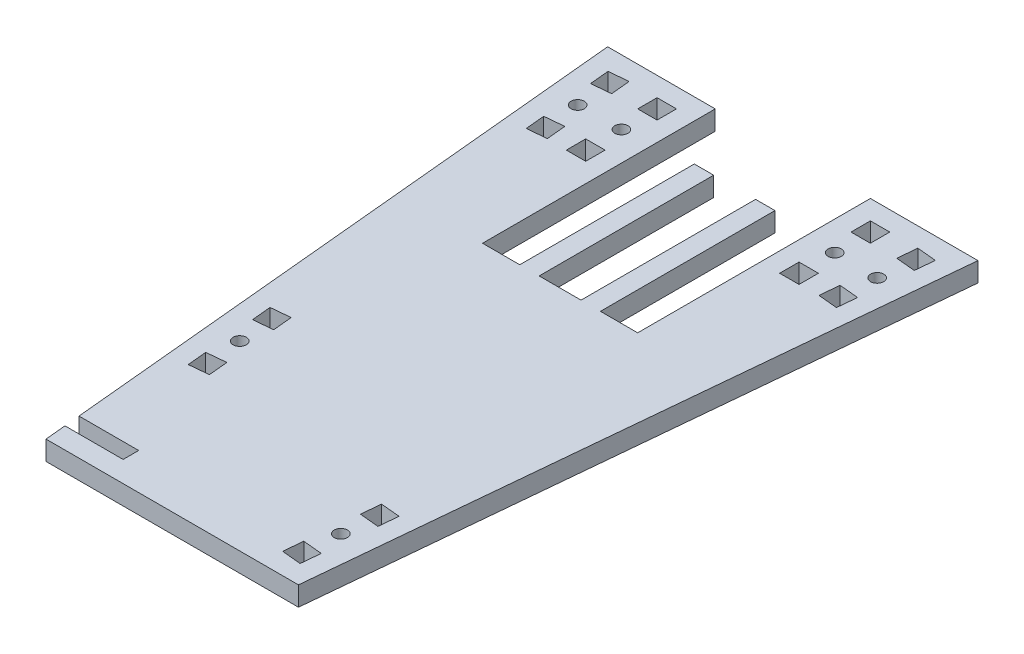
SolidWorks part; units mm, degrees
ref_plane "Front Plane" through (0, 0, 0) normal (0, 0, 1) x (1, 0, 0)
ref_plane "Top Plane" through (0, 0, 0) normal (0, 1, 0) x (1, 0, 0)
ref_plane "Right Plane" through (0, 0, 0) normal (1, 0, 0) x (0, 0, -1)
sketch "Sketch1" plane through (0, 0, 0) normal (0, 1, 0) x (1, 0, 0)
  line L0 (0, 0) -> (0, -183.008) construction
  line L1 (-47.8759, 76.2) -> (-25.4, 76.2)
  line L2 (47.8759, 76.2) -> (28.575, -127) construction
  line L3 (-47.8759, 76.2) -> (-28.575, -127) construction
  line L4 (38.1, 40.132) -> (44.45, 40.132) construction
  line L5 (-47.8759, 76.2) -> (-60.6331, 76.2)
  line L6 (-41.9836, -120.142) -> (-11.3629, -120.142) construction
  line L7 (-57.15, 0) -> (57.15, 0) construction
  line L8 (31.75, 76.2) -> (31.75, 40.132) construction
  line L9 (-31.75, 76.2) -> (-31.75, 40.132) construction
  line L10 (6.858, 57.15) -> (6.858, 0) construction
  line L11 (-6.858, 57.15) -> (-6.858, 0) construction
  line L12 (-6.858, 57.15) -> (-6.858, 0)
  line L13 (-6.858, 0) -> (6.858, 0)
  line L14 (6.858, 0) -> (6.858, 57.15)
  line L15 (6.858, 57.15) -> (13.208, 57.15)
  line L16 (-41.9836, -120.142) -> (-22.9336, -120.142)
  line L17 (-22.9336, -120.142) -> (-22.9336, -115.062)
  line L18 (13.208, 57.15) -> (13.208, 0)
  line L19 (13.208, 0) -> (25.4, 0)
  line L20 (25.4, 0) -> (25.4, 76.2)
  line L21 (25.4, 76.2) -> (47.8759, 76.2)
  line L22 (-25.4, 0) -> (-25.4, 76.2)
  line L23 (-13.208, 0) -> (-25.4, 0)
  line L24 (-13.208, 57.15) -> (-13.208, 0)
  line L25 (-6.858, 0) -> (-6.858, 57.15)
  line L26 (-13.208, 57.15) -> (-6.858, 57.15)
  line L27 (-22.9336, -115.062) -> (-42.4661, -115.062)
  line L28 (-41.9836, -120.142) -> (-41.3322, -127)
  line L29 (47.8759, 76.2) -> (60.6331, 76.2)
  line L30 (60.6331, 76.2) -> (41.3322, -127)
  line L31 (-28.575, -127) -> (0, -127)
  line L32 (0, -127) -> (28.575, -127)
  line L33 (28.575, -127) -> (41.3322, -127)
  line L34 (-60.6331, 76.2) -> (-42.4661, -115.062)
  line L35 (-28.575, -127) -> (-41.3322, -127)
  line L36 (-38.5725, -88.9) -> (-32.251, -88.2995) construction
  line L37 (34.9536, -127) -> (28.632, -126.3995) construction
  line L38 (35.554, -120.6785) -> (34.9536, -127) construction
  line L39 (-39.173, -82.5785) -> (-38.5725, -88.9) construction
  point P0 (0, 0)
  line B0 (34.925, 40.132) -> (34.925, 69.85) construction
  line B1 (32.766, 54.991) -> (37.084, 54.991) construction
  line B2 (31.75, 63.5) -> (38.1, 63.5)
  line B3 (31.75, 63.5) -> (31.75, 69.85)
  line B4 (31.75, 69.85) -> (38.1, 69.85)
  line B5 (38.1, 63.5) -> (38.1, 69.85)
  line B6 (31.75, 63.5) -> (38.1, 69.85) construction
  line B7 (31.75, 69.85) -> (38.1, 63.5) construction
  line B8 (31.75, 40.132) -> (38.1, 46.482) construction
  line B9 (31.75, 46.482) -> (38.1, 40.132) construction
  line B10 (38.1, 46.482) -> (38.1, 40.132)
  line B11 (31.75, 40.132) -> (38.1, 40.132)
  line B12 (31.75, 46.482) -> (31.75, 40.132)
  line B13 (31.75, 46.482) -> (38.1, 46.482)
  circle B14 centre (34.925, 54.991) radius 2.159
  line B15 (-34.925, 40.132) -> (-34.925, 69.85) construction
  line B16 (-32.766, 54.991) -> (-37.084, 54.991) construction
  line B17 (-31.75, 63.5) -> (-38.1, 63.5)
  line B18 (-31.75, 63.5) -> (-31.75, 69.85)
  line B19 (-31.75, 69.85) -> (-38.1, 69.85)
  line B20 (-38.1, 63.5) -> (-38.1, 69.85)
  line B21 (-31.75, 63.5) -> (-38.1, 69.85) construction
  line B22 (-31.75, 69.85) -> (-38.1, 63.5) construction
  line B23 (-31.75, 40.132) -> (-38.1, 46.482) construction
  line B24 (-31.75, 46.482) -> (-38.1, 40.132) construction
  line B25 (-38.1, 46.482) -> (-38.1, 40.132)
  line B26 (-31.75, 40.132) -> (-38.1, 40.132)
  line B27 (-31.75, 46.482) -> (-31.75, 40.132)
  line B28 (-31.75, 46.482) -> (-38.1, 46.482)
  circle B29 centre (-34.925, 54.991) radius 2.159
  line B30 (47.6261, 39.9934) -> (50.4362, 69.5782) construction
  line B31 (46.8819, 54.99) -> (51.1805, 54.5817) construction
  line B32 (46.675, 63.5569) -> (52.9966, 62.9565)
  line B33 (46.675, 63.5569) -> (47.2755, 69.8785)
  line B34 (47.2755, 69.8785) -> (53.597, 69.278)
  line B35 (52.9966, 62.9565) -> (53.597, 69.278)
  line B36 (46.675, 63.5569) -> (53.597, 69.278) construction
  line B37 (47.2755, 69.8785) -> (52.9966, 62.9565) construction
  line B38 (44.4654, 40.2936) -> (51.3873, 46.0147) construction
  line B39 (45.0658, 46.6152) -> (50.7869, 39.6932) construction
  line B40 (51.3873, 46.0147) -> (50.7869, 39.6932)
  line B41 (44.4654, 40.2936) -> (50.7869, 39.6932)
  line B42 (45.0658, 46.6152) -> (44.4654, 40.2936)
  line B43 (45.0658, 46.6152) -> (51.3873, 46.0147)
  circle B44 centre (49.0312, 54.7858) radius 2.159
  line B45 (32.3933, -120.3782) -> (35.2034, -90.7934) construction
  line B46 (31.649, -105.3817) -> (35.9476, -105.79) construction
  line B47 (31.4421, -96.8147) -> (37.7637, -97.4152)
  line B48 (31.4421, -96.8147) -> (32.0426, -90.4932)
  line B49 (32.0426, -90.4932) -> (38.3641, -91.0936)
  line B50 (37.7637, -97.4152) -> (38.3641, -91.0936)
  line B51 (31.4421, -96.8147) -> (38.3641, -91.0936) construction
  line B52 (32.0426, -90.4932) -> (37.7637, -97.4152) construction
  line B53 (29.2325, -120.078) -> (36.1545, -114.3569) construction
  line B54 (29.8329, -113.7565) -> (35.554, -120.6785) construction
  line B55 (36.1545, -114.3569) -> (35.554, -120.6785)
  line B56 (29.2325, -120.078) -> (35.554, -120.6785)
  line B57 (29.8329, -113.7565) -> (29.2325, -120.078)
  line B58 (29.8329, -113.7565) -> (36.1545, -114.3569)
  circle B59 centre (33.7983, -105.5858) radius 2.159
  line B60 (-36.0122, -82.2782) -> (-38.8223, -52.6934) construction
  line B61 (-35.2679, -67.2817) -> (-39.5666, -67.69) construction
  line B62 (-35.0611, -58.7147) -> (-41.3826, -59.3152)
  line B63 (-35.0611, -58.7147) -> (-35.6615, -52.3932)
  line B64 (-35.6615, -52.3932) -> (-41.9831, -52.9936)
  line B65 (-41.3826, -59.3152) -> (-41.9831, -52.9936)
  line B66 (-35.0611, -58.7147) -> (-41.9831, -52.9936) construction
  line B67 (-35.6615, -52.3932) -> (-41.3826, -59.3152) construction
  line B68 (-32.8514, -81.978) -> (-39.7734, -76.2569) construction
  line B69 (-33.4519, -75.6565) -> (-39.173, -82.5785) construction
  line B70 (-39.7734, -76.2569) -> (-39.173, -82.5785)
  line B71 (-32.8514, -81.978) -> (-39.173, -82.5785)
  line B72 (-33.4519, -75.6565) -> (-32.8514, -81.978)
  line B73 (-33.4519, -75.6565) -> (-39.7734, -76.2569)
  circle B74 centre (-37.4172, -67.4858) radius 2.159
  line B75 (-47.6261, 39.9934) -> (-50.4362, 69.5782) construction
  line B76 (-46.8819, 54.99) -> (-51.1805, 54.5817) construction
  line B77 (-46.675, 63.5569) -> (-52.9966, 62.9565)
  line B78 (-46.675, 63.5569) -> (-47.2755, 69.8785)
  line B79 (-47.2755, 69.8785) -> (-53.597, 69.278)
  line B80 (-52.9966, 62.9565) -> (-53.597, 69.278)
  line B81 (-46.675, 63.5569) -> (-53.597, 69.278) construction
  line B82 (-47.2755, 69.8785) -> (-52.9966, 62.9565) construction
  line B83 (-44.4654, 40.2936) -> (-51.3873, 46.0147) construction
  line B84 (-45.0658, 46.6152) -> (-50.7869, 39.6932) construction
  line B85 (-51.3873, 46.0147) -> (-50.7869, 39.6932)
  line B86 (-44.4654, 40.2936) -> (-50.7869, 39.6932)
  line B87 (-45.0658, 46.6152) -> (-44.4654, 40.2936)
  line B88 (-45.0658, 46.6152) -> (-51.3873, 46.0147)
  circle B89 centre (-49.0312, 54.7858) radius 2.159
  dimension "D1" = 63.5
  dimension "D2" = 6.35
  dimension "D3" = 6.858
  dimension "D4" = 57.15
  dimension "D5" = 6.858
  dimension "D6" = 5.08
  dimension "D7" = 19.05
  dimension "D8" = 203.2
  dimension "D9" = 6.35
  dimension "D10" = 6.35
  dimension "D11" = 6.35
  dimension "D12" = 76.2
  dimension "D13" = 6.35
  dimension "D14" = 6.35
  dimension "D15" = 38.1
  dimension "D16" = 127
  dimension "D17" = 93.1039
  dimension "D18" = 131.3754
  dimension "D19" = 19.05
sketch_block_instance "Female T-Slot Assembly-1"
sketch_block "Female T-Slot Assembly" parameters "D4"=4.318, "D1"=6.35, "D2"=6.35, "D3"=6.35
sketch_block_instance "Female T-Slot Assembly-3"
sketch_block_instance "Female T-Slot Assembly-1"
sketch_block_instance "Female T-Slot Assembly-14"
sketch_block_instance "Female T-Slot Assembly-16"
sketch_block_instance "Female T-Slot Assembly-17"
extrude "Boss-Extrude1" add sketch "Sketch1" along normal blind 6.35
equation "\"Ball Diameter\"= 1.75in"
equation "\"Ball Radius\" = \"Ball Diameter\"/2"
equation "\"Sheet Thickness\"= 0.25in"
equation "\"Screw Diameter\"= .17in"
equation "\"Robot Diameter\"= 14in"
equation "\"Castor Screw Diameter\"= 0.22in"
equation "\"Wheel Diameter\" = 4in"
equation "\"Nut Diameter\" = 8.4mm"
equation "\"Nut Height\" = 2.9mm"
equation "\"Screw Height\" = 0.55in"
equation "\"Pulley Diameter\" = 1in"
equation "\"Reactor Height\" = 14in"
equation "\"Elevator Height\" = 11.5in"
equation "\"Elevator Width\" = \"Ball Diameter\" + 0.25in"
equation "\"Elevator Bearing Diameter\" = sqr(2*(\"Sheet Thickness\"^2)) + 0.2in"
equation "\"Elevator Axle Endcap Diameter\" = \"Pulley Diameter\" + 0.25in"
equation "\"Elevator Axle Length\" = \"Elevator Width\" + 8*\"Sheet Thickness\""
equation "\"Elevator Clearance from Axis\" = 3.28in"
equation "\"Elevator Horizontal Clearance\" = \"Elevator Width\" + 0.5in"
equation "\"Claw Horizontal Seperation\" = (\"Elevator Width\"/2) - (1.5 * \"Sheet Thickness\") - 0.15in"
equation "\"Claw Radius\" = \"Ball Radius\" + 0.1in"
equation "\"Castor Wheel Height\" = 1.25in"
equation "\"Length of Chute\" = 8in"
equation "\"D4@Sketch1\"=\"Ball Diameter\" + 0.5in"
equation "\"D8@Sketch1\"=\"Length of Chute\""
